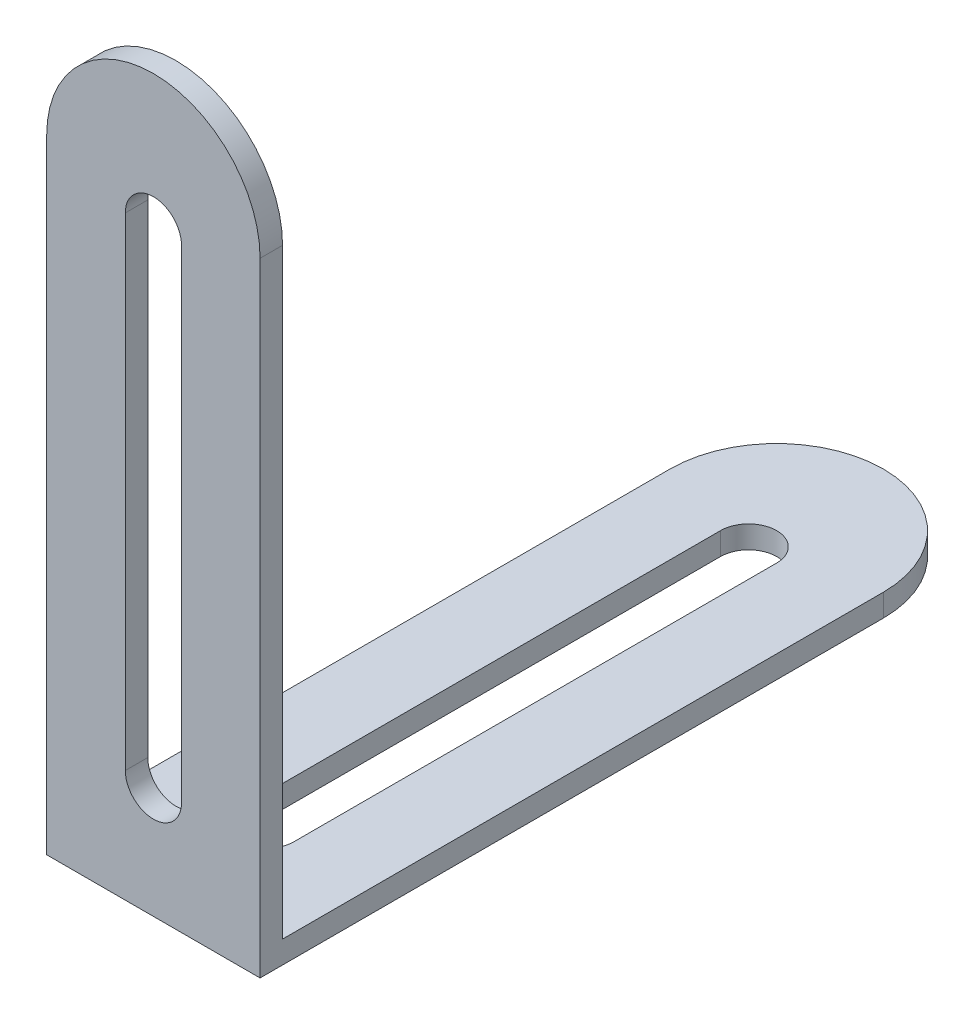
SolidWorks part; units mm, degrees
material "1023 碳钢板 (SS)"
ref_plane "前视基准面" through (0, 0, 0) normal (0, 0, 1) x (1, 0, 0)
ref_plane "上视基准面" through (0, 0, 0) normal (0, 1, 0) x (1, 0, 0)
ref_plane "右视基准面" through (0, 0, 0) normal (1, 0, 0) x (0, 0, -1)
sketch "草图1" plane through (0, 0, 0) normal (0, 0, 1) x (1, 0, 0)
  line L0 (0, 53) -> (0, 10) construction
  line L1 (-9.5, 0) -> (9.5, 0)
  line L2 (-9.5, 0) -> (-9.5, 55.5)
  line L4 (9.5, 0) -> (9.5, 55.5)
  line L5 (-9.5, 0) -> (9.5, 0)
  line L6 (-9.5, 0) -> (-9.5, 2.5)
  line L7 (-9.5, 2.5) -> (9.5, 2.5)
  line L8 (9.5, 0) -> (9.5, 2.5)
  line L9 (2.5, 53) -> (2.5, 10)
  line L10 (-2.5, 53) -> (-2.5, 10)
  arc A0 (9.5, 55.5) -> (-9.5, 55.5) centre (0, 55.5) ccw
  arc A3 (2.5, 53) -> (-2.5, 53) centre (0, 53) ccw
  arc A4 (-2.5, 10) -> (2.5, 10) centre (0, 10) ccw
  point P0 (0, 0)
  point P3 (0, 10)
  point P6 (0, 55.5)
  point P8 (0, 53)
  point P11 (0, 31.5)
  dimension "D4" = 2.5
  dimension "D1" = 9.5
  dimension "D2" = 55.5
  dimension "D3" = 19
  dimension "D5" = 9.5
  dimension "D6" = 10
  dimension "D7" = 43
  dimension "D10" = 2.5
extrude "凸台-拉伸1" add sketch "草图1" along normal blind 2
sketch "草图2" plane through (0, 0, 0) normal (0, 1, 0) x (1, 0, 0)
  line L0 (-9.5, -2) -> (9.5, -2) construction
  line L1 (-9.5, -2) -> (9.5, -2)
  line L2 (-9.5, -2) -> (-9.5, 53.5)
  line L4 (9.5, -2) -> (9.5, 53.5)
  line L5 (0, 8) -> (0, 51) construction
  line L6 (-2.5, 8) -> (-2.5, 51)
  line L7 (2.5, 8) -> (2.5, 51)
  arc A0 (9.5, 53.5) -> (-9.5, 53.5) centre (0, 53.5) ccw
  arc A3 (-2.5, 8) -> (2.5, 8) centre (0, 8) ccw
  arc A4 (2.5, 51) -> (-2.5, 51) centre (0, 51) ccw
  point P10 (0, 29.5)
  dimension "D2" = 9.5
  dimension "D4" = 2.5
  dimension "D5" = 8
  dimension "D1" = 55.5
  dimension "D3" = 19
  dimension "D6" = 43
extrude "凸台-拉伸2" add sketch "草图2" along normal blind 2
